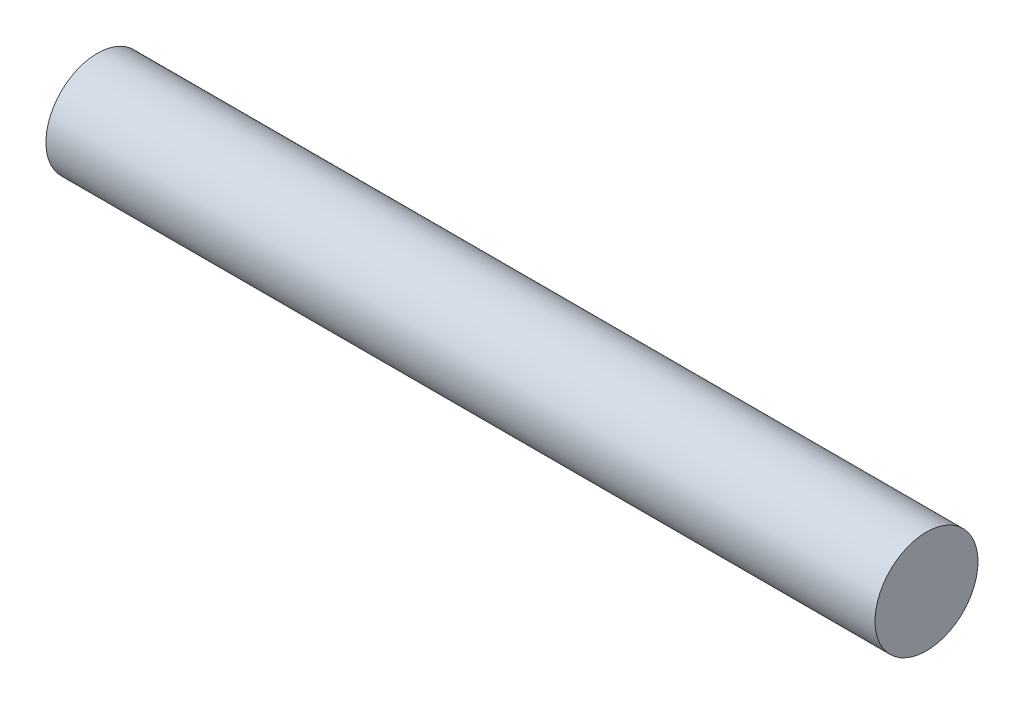
SolidWorks part; units mm, degrees
ref_plane "Front Plane" through (0, 0, 0) normal (0, 0, 1) x (1, 0, 0)
ref_plane "Top Plane" through (0, 0, 0) normal (0, 1, 0) x (1, 0, 0)
ref_plane "Right Plane" through (0, 0, 0) normal (1, 0, 0) x (0, 0, -1)
sketch "Sketch2" plane through (0, 0, 0) normal (1, 0, 0) x (0, 0, -1)
  circle A0 centre (0, 0) radius 102.108
  dimension "D1" = 204.216
extrude "Boss-Extrude1" add sketch "Sketch2" along normal blind 1644.142
